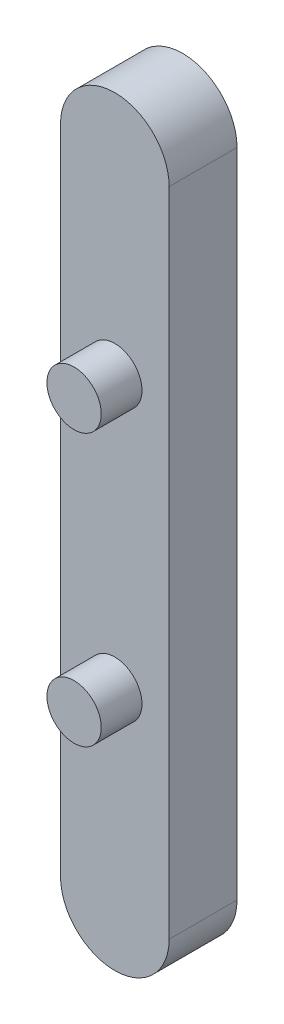
SolidWorks part; units mm, degrees
ref_plane "Plan de face" through (0, 0, 0) normal (0, 0, 1) x (1, 0, 0)
ref_plane "Plan de dessus" through (0, 0, 0) normal (0, 1, 0) x (1, 0, 0)
ref_plane "Plan de droite" through (0, 0, 0) normal (1, 0, 0) x (0, 0, -1)
sketch "Esquisse1" plane through (0, 0, 0) normal (0, 0, 1) x (1, 0, 0)
  line L0 (0, 0) -> (0, 24) construction
  line L1 (-2, 0) -> (-2, 24)
  line L2 (2, 0) -> (2, 24)
  arc A0 (-2, 0) -> (2, 0) centre (0, 0) ccw
  arc A1 (2, 24) -> (-2, 24) centre (0, 24) ccw
  point P3 (0, 12)
  point P8 (0, 26)
  point P9 (0, -2)
  dimension "D1" = 28
  dimension "D2" = 4
extrude "Boss.-Extru.1" add sketch "Esquisse1" along normal blind 2.5
sketch "Esquisse2" plane through (0, 0, 2.5) normal (0, 0, 1) x (1, 0, 0)
  line L0 (0, 17) -> (0, 7) construction
  line L1 (0, 12) -> (2, 12) construction
  line L2 (2, 0) -> (2, 24) construction
  line L3 (0, 26) -> (0, -2) construction
  arc A0 (2, 24) -> (-2, 24) centre (0, 24) ccw construction
  arc A1 (-2, 0) -> (2, 0) centre (0, 0) ccw construction
  circle A2 centre (0, 17) radius 1
  circle A3 centre (0, 7) radius 1
  dimension "D1" = 2
  dimension "D2" = 2
  dimension "D3" = 10
extrude "Boss.-Extru.2" add sketch "Esquisse2" along normal blind 1.5
